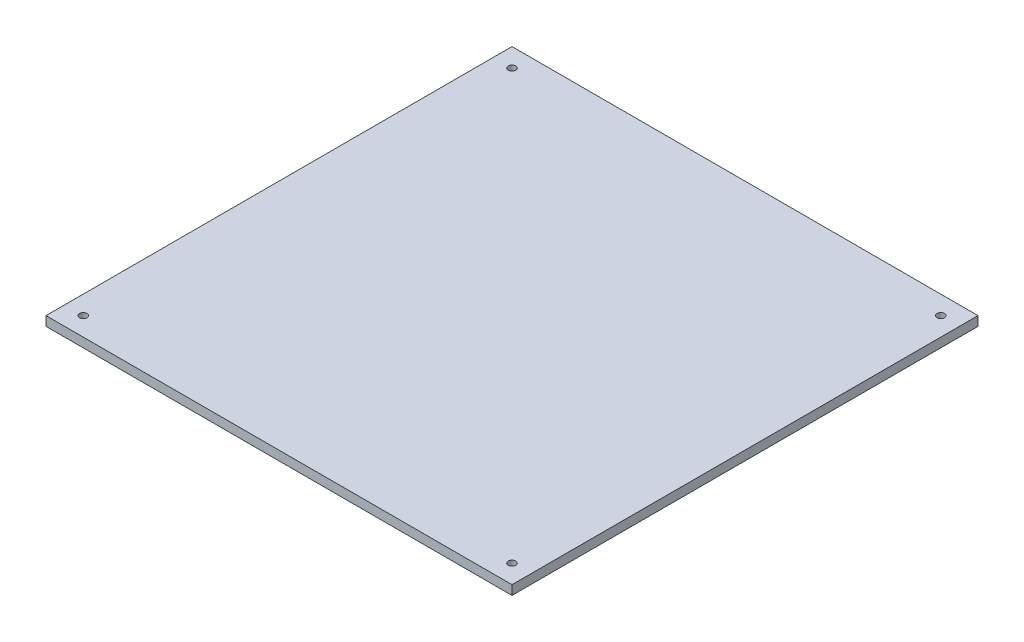
SolidWorks part; units mm, degrees
ref_plane "Płaszczyzna przednia" through (0, 0, 0) normal (0, 0, 1) x (1, 0, 0)
ref_plane "Płaszczyzna górna" through (0, 0, 0) normal (0, 1, 0) x (1, 0, 0)
ref_plane "Płaszczyzna prawa" through (0, 0, 0) normal (1, 0, 0) x (0, 0, -1)
sketch "Szkic1" plane through (0, 0, 0) normal (0, 1, 0) x (1, 0, 0)
  line L1 (-250, -250) -> (250, -250)
  line L2 (-250, -250) -> (-250, 250)
  line L3 (-250, 250) -> (250, 250)
  line L4 (250, -250) -> (250, 250)
  line L5 (-250, -250) -> (250, 250) construction
  line L6 (-250, 250) -> (250, -250) construction
  point P0 (0, 0)
  dimension "D1" = 500
  dimension "D2" = 500
extrude "Dodanie-wyciągnięcie1" add sketch "Szkic1" along normal blind 10
sketch "Szkic2" plane through (0, 10, 0) normal (0, 1, 0) x (1, 0, 0)
  line L0 (250, 250) -> (-250, 250) construction
  line L1 (-250, 250) -> (-250, -250) construction
  circle A0 centre (-230, 230) radius 4
  circle A1 centre (230, 230) radius 4
  circle A2 centre (230, -230) radius 4
  circle A3 centre (-230, -230) radius 4
  point P2 (0, 0)
  point P13 (0, 0)
  dimension "D1" = 8
  dimension "D2" = 20
  dimension "D4" = 20
  dimension "D3" = 4
extrude "Wytnij-wyciągnięcie1" cut sketch "Szkic2" against normal through all
